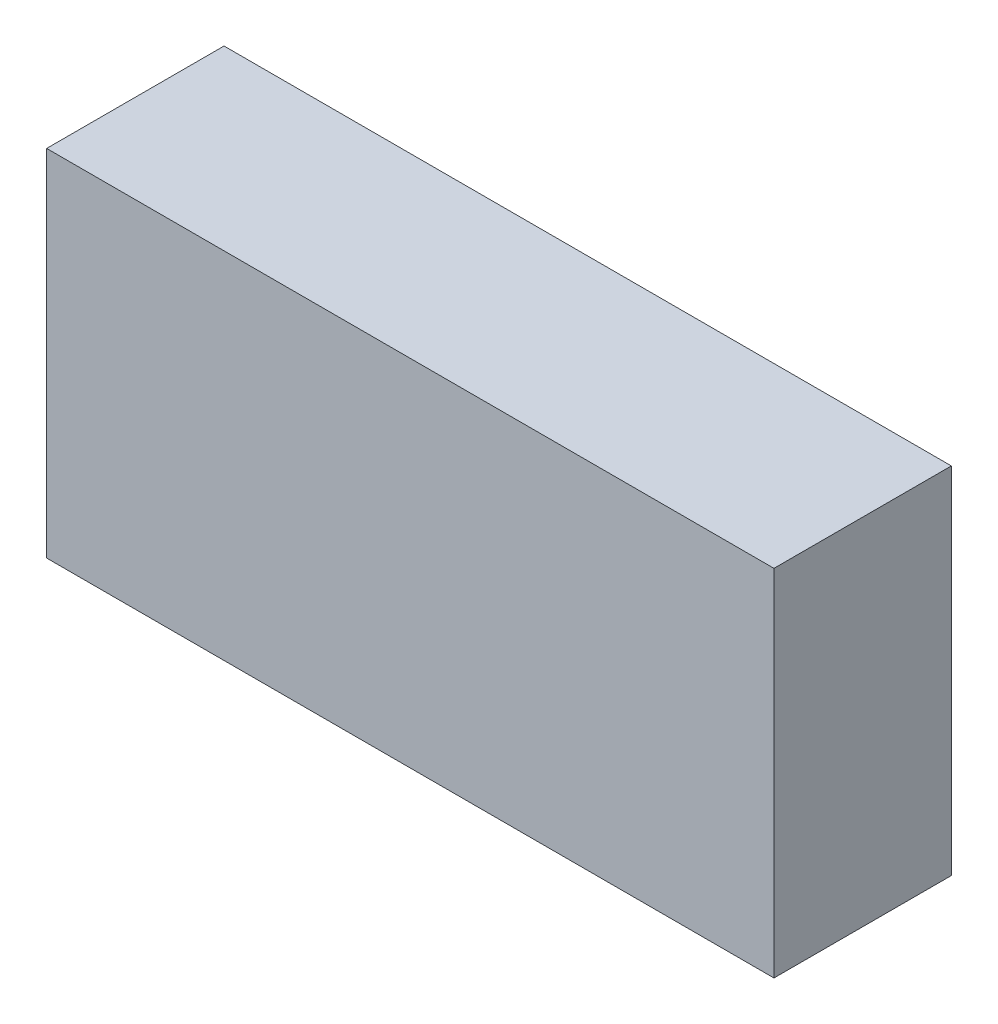
SolidWorks part; units mm, degrees
ref_plane "Front Plane" through (0, 0, 0) normal (0, 0, 1) x (1, 0, 0)
ref_plane "Top Plane" through (0, 0, 0) normal (0, 1, 0) x (1, 0, 0)
ref_plane "Right Plane" through (0, 0, 0) normal (1, 0, 0) x (0, 0, -1)
sketch "RectangleSketch" plane through (0, 0, 0) normal (0, 0, 1) x (1, 0, 0)
  line L1 (0, 0) -> (41, 0)
  line L2 (0, 0) -> (0, 20)
  line L3 (0, 20) -> (41, 20)
  line L4 (41, 0) -> (41, 20)
  dimension "width_mm" = 41
  dimension "height_mm" = 20
extrude "BlindBoss" add sketch "RectangleSketch" along normal blind 10 separate body
